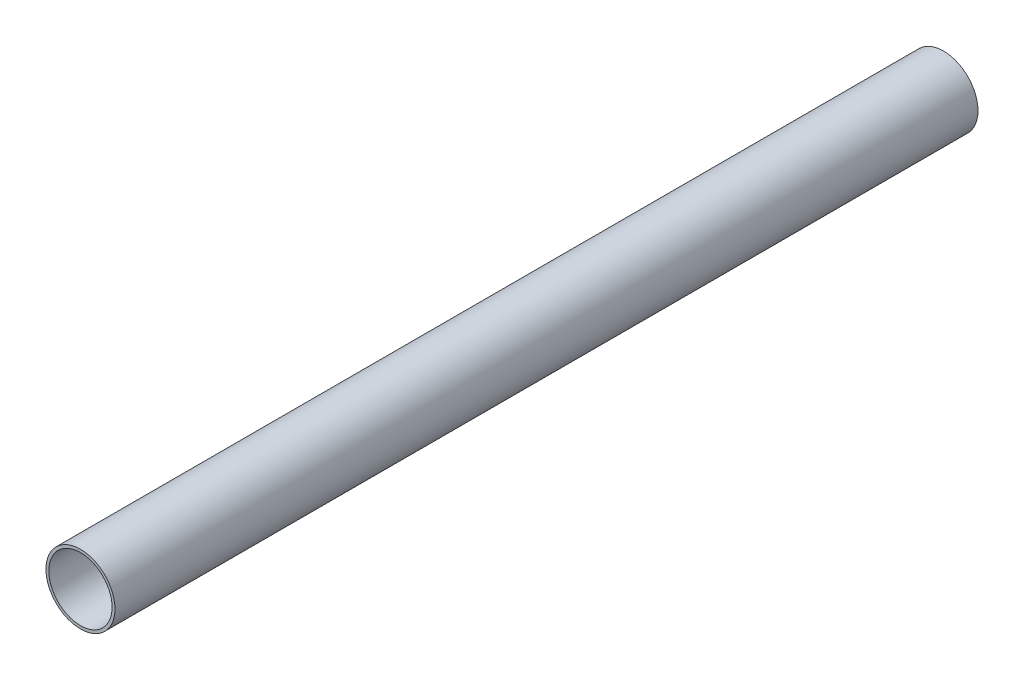
SolidWorks part; units mm, degrees
ref_plane "前视基准面" through (0, 0, 0) normal (0, 0, 1) x (1, 0, 0)
ref_plane "上视基准面" through (0, 0, 0) normal (0, 1, 0) x (1, 0, 0)
ref_plane "右视基准面" through (0, 0, 0) normal (1, 0, 0) x (0, 0, -1)
other "Configuration Table"
sketch "草图1" plane through (0, 0, 0) normal (0, 0, 1) x (1, 0, 0)
  circle A0 centre (0, 0) radius 3
  dimension "D1" = 6
extrude "凸台-拉伸1" add sketch "草图1" along normal blind 75
sketch "草图2" plane through (0, 0, 0) normal (0, 0, -1) x (-1, 0, 0)
  circle A0 centre (0, 0) radius 2.75
  dimension "D1" = 5.5
extrude "切除-拉伸1" cut sketch "草图2" against normal blind 75
